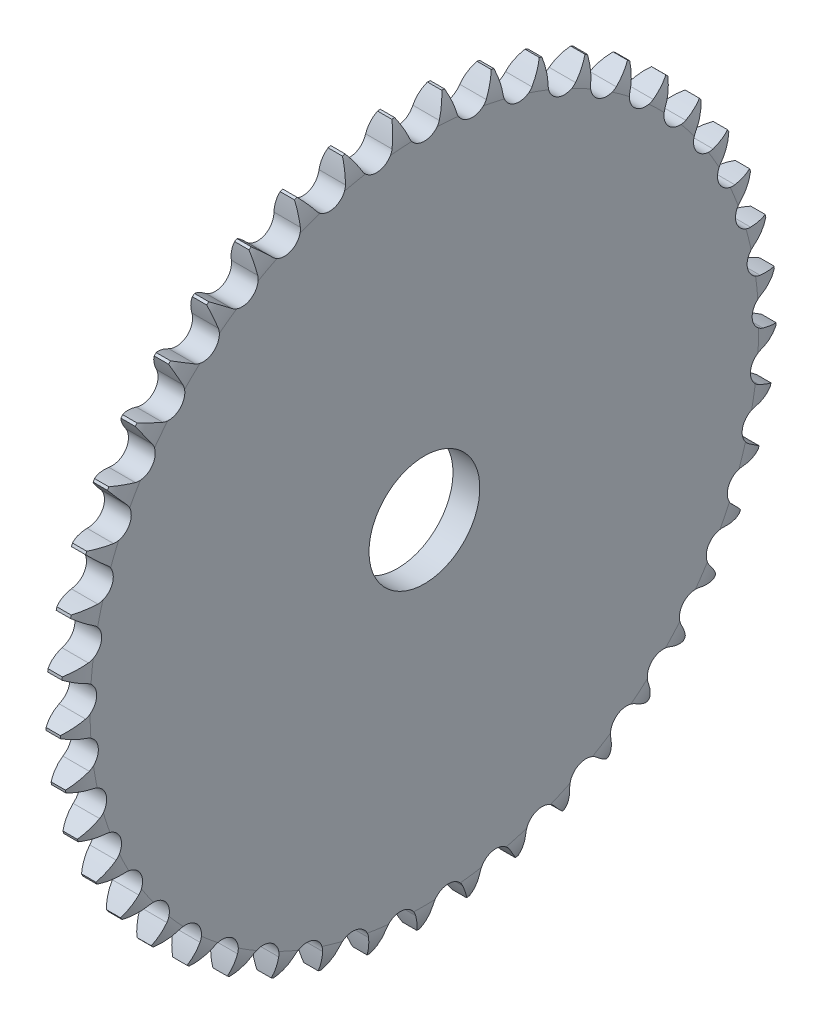
SolidWorks part; units mm, degrees
ref_plane "Plane1" through (0, 0, 0) normal (0, 0, 1) x (1, 0, 0)
ref_plane "Plane2" through (0, 0, 0) normal (0, 1, 0) x (1, 0, 0)
ref_plane "Plane3" through (0, 0, 0) normal (1, 0, 0) x (0, 0, -1)
sketch "Clipboard" plane through (0, 0, 0) normal (0, 1, 0) x (1, 0, 0)
  line L0 (0, 0) -> (6.7352, -6.7352)
  line L1 (-15, 0) -> (100, 0) construction
  line L2 (0, 0) -> (-0.8203, 0.9272)
  line L3 (0, 0) -> (-8.8973, 3.4006)
  line L4 (0, 0) -> (2.192, 2.192)
  line L5 (0, 0) -> (-46.8476, -17.4728)
  line L6 (0, 0) -> (-4.4098, -2.9753)
  line L7 (-0.8203, 0.9272) -> (33.9129, 36.8945)
  line L8 (-76.2, 38.1) -> (-72.9, 38.1)
  line L9 (-73.3242, 40.7328) -> (-72.926, 40.7699)
  line L10 (-73.4529, 9.1872) -> (-63.2129, 9.1872)
  circle A0 centre (0, 0) radius 3.175
  circle A1 centre (0, 0) radius 37.5
  circle A2 centre (0, 0) radius 37.5
  dimension "Dr" = 6.35
  dimension "MHD" = 75
  dimension "Hub_dia" = 75
  dimension "Num_teeth" = 45
  dimension "Pitch" = 9.525
  dimension "Width" = 3.1
  dimension "Side_relief" = 1.238
  dimension "Side_radius" = 9.525
  dimension "Overall_len" = 50
  dimension "Show_teeth" = 45
  dimension "Thickness" = 5.3196
  dimension "OAL" = 50.0005
  dimension "T_dim" = 3.3
  dimension "Fillet_rad" = 0.4
  dimension "Face_width" = 5.32
  dimension "Num_strands" = 1
  dimension "Transv_pitch" = 10.24
  dimension "Plate_wid" = 8.26
sketch "BasProSke" plane through (0, 0, 0) normal (0, 1, 0) x (1, 0, 0)
  line L0 (-10, 0) -> (60, 0) construction
  line L1 (0, 0) -> (0, 66.3555)
  line L2 (0, 0) -> (5.3196, 0)
  line L3 (5.3196, 0) -> (5.3196, 66.3555)
  line L4 (4.0816, 71.0514) -> (1.238, 71.0514)
  arc A0 (0, 66.3555) -> (1.238, 71.0514) centre (9.525, 66.3555) cw
  arc A1 (5.3196, 66.3555) -> (4.0816, 71.0514) centre (-4.2054, 66.3555) ccw
  dimension "Thickness" = 5.3196
  dimension "D1" = 9.525
  dimension "G1" = 1.238
  dimension "G2" = 1.238
  dimension "Diameter" = 142.1027
revolve "Base-Revolve" add sketch "BasProSke" angle 360 about L0
sketch "TooCutSke" plane through (0, 0, 0) normal (1, 0, 0) x (0, 0, -1)
  line L0 (0, 68.305) -> (2.9938, 67.1558) construction
  line L1 (0, 0) -> (0, 107) construction
  line L2 (0, 68.305) -> (-10, 68.305) construction
  line L3 (0, 68.305) -> (-2.9938, 67.1558) construction
  arc A0 (2.9938, 67.1558) -> (4.9391, 71.3807) centre (36.429, 54.3212) cw
  arc A1 (2.9938, 67.1558) -> (-2.9938, 67.1558) centre (0, 68.305) cw
  arc A2 (-2.9938, 67.1558) -> (-4.9391, 71.3807) centre (-36.429, 54.3212) ccw
  arc A3 (4.9391, 71.3807) -> (-4.9391, 71.3807) centre (0, 0) ccw
  dimension "R1" = 3.2067
  dimension "R2" = 35.814
  dimension "Overcut" = 71.5514
  dimension "Seat_radius" = 68.305
  dimension "X" = 138
extrude "ToothCut" cut sketch "TooCutSke" along normal through all
pattern_circular "TeethCuts" count 45 every 8 about axis through (-10, 0, 0) along (1, 0, 0) of "ToothCut"
sketch "HubNeaOneSke" plane through (0, 0, 0) normal (-1, 0, 0) x (0, 0, 1)
  circle A0 centre (0, 0) radius 37.5
  dimension "Diameter" = 75
extrude "HubNearOne" [suppressed] add sketch "HubNeaOneSke" along normal blind 44.6809
fillet "HubNearOneFillet" [suppressed] radius 0.4
sketch "HubNeaBotSke" plane through (0, 0, 0) normal (-1, 0, 0) x (0, 0, 1)
  circle A0 centre (0, 0) radius 37.5
  dimension "Diameter" = 75
extrude "HubNearBoth" [suppressed] add sketch "HubNeaBotSke" along normal blind 22.3405
fillet "HubNearBothFillet" [suppressed] radius 0.4
ref_plane "FarPln" through (5.3196, 0, 0) normal (1, 0, 0) x (0, 0, -1)
sketch "HubFarSke" plane through (5.3196, 0, 0) normal (1, 0, 0) x (0, 0, -1)
  circle A0 centre (0, 0) radius 37.5
  dimension "Diameter" = 75
extrude "HubFar" [suppressed] add sketch "HubFarSke" along normal blind 22.3405
fillet "HubFarFillet" [suppressed] radius 0.4
sketch "BorSke" plane through (0, 0, 0) normal (1, 0, 0) x (0, 0, -1)
  circle A0 centre (0, 0) radius 11
  dimension "Diameter" = 22
extrude "Bore" cut sketch "BorSke" along normal mid plane 100.001
sketch "KeySke" plane through (0, 0, 0) normal (1, 0, 0) x (0, 0, -1)
  line L0 (-3, 0) -> (-3, 14.3)
  line L1 (-3, 14.3) -> (3, 14.3)
  line L2 (3, 14.3) -> (3, 0)
  line L3 (0, 0) -> (0, 34) construction
  line L4 (-3, 0) -> (3, 0)
  dimension "Offset" = 14.3
  dimension "Width" = 6
extrude "Keyway" [suppressed] cut sketch "KeySke" along normal mid plane 100.001
pattern_circular "Keyway2" [suppressed] count 2 every 90 about axis through (-10, 0, 0) along (1, 0, 0)
equation "' \"Pitch@Clipboard\" = 12.7"
equation "' \"Num_strands@Clipboard\" = 1"
equation "' \"Num_teeth@Clipboard\" = 9"
equation "' \"Hub_dia@Clipboard\" = 50"
equation "' \"Overall_len@Clipboard\" = 3"
equation "' \"Diameter@BorSke\" = 12"
equation "' \"T_dim@Clipboard\" = 1"
equation "' \"Width@KeySke\" = 2"
equation "' \"Dr@Clipboard\" = 8.51"
equation "' \"Face_width@Clipboard\" = 7.2"
equation "' \"Side_radius@Clipboard\" = 12.7"
equation "' \"Side_relief@Clipboard\" = 1.27"
equation "' \"Transv_pitch@Clipboard\" = 13.92"
equation "' \"Show_teeth@Clipboard\" = 9"
equation "' \"Fillet_rad@Clipboard\" = 0.6"
equation "' \"Plate_wid@Clipboard\" = 11.8"
equation "\"Num_teeth@Clipboard\" = int( \"Num_teeth@Clipboard\" )"
equation "\"Num_teeth@Clipboard\" = ((sgn( \"Num_teeth@Clipboard\" - 5.0)+1)*( \"Num_teeth@Clipboard\" - 5.0))/2 +5.0"
equation "\"Num_teeth@Clipboard\" = ((sgn( \"Num_teeth@Clipboard\" - 200.0)-1)*( \"Num_teeth@Clipboard\" - 200.0))/-2 +200.0"
equation "\"MHD@Clipboard\" = \"Pitch@Clipboard\" * (1.0 / tan(3.14159265 / \"Num_teeth@Clipboard\" )) - 1.04 * \"Plate_wid@Clipboard\" - 0.76"
equation "\"Thickness@Clipboard\"  = \"Face_width@Clipboard\" + (\"Num_strands@Clipboard\" - 1) * \"Transv_pitch@Clipboard\""
equation "\"OAL@Clipboard\" = \"Thickness@Clipboard\" + 2 * \"Fillet_rad@Clipboard\" + 1"
equation "\"MHD@Clipboard\" = ((sgn( \"MHD@Clipboard\" - \"Hub_dia@Clipboard\" )-1)*( \"MHD@Clipboard\" - \"Hub_dia@Clipboard\" ))/-2+ \"Hub_dia@Clipboard\""
equation "\"OAL@Clipboard\" = ((sgn( \"OAL@Clipboard\" - \"Overall_len@Clipboard\" )+1)*( \"OAL@Clipboard\" - \"Overall_len@Clipboard\" ))/2 + \"Overall_len@Clipboard\" + 0.0005"
equation "\"Num_teeth@TeethCuts\" = int( \"Show_teeth@Clipboard\" ) + 1"
equation "\"Num_teeth@TeethCuts\" = ((sgn( \"Num_teeth@TeethCuts\" - \"Num_teeth@Clipboard\" )-1)*( \"Num_teeth@TeethCuts\" - \"Num_teeth@Clipboard\" ))/-2+ \"Num_teeth@Clipboard\""
equation "\"Num_teeth@TeethCuts\" = ((sgn( \"Num_teeth@TeethCuts\" - 2.0)+1)*( \"Num_teeth@TeethCuts\" - 2.0))/2 +2.0"
equation "\"Angle@TeethCuts\" = 360.0 / \"Num_teeth@Clipboard\""
equation "\"Seat_radius@TooCutSke\" = ( \"Pitch@Clipboard\" / 2.0) / sin(3.14159265 / \"Num_teeth@Clipboard\" ) - \"Dr@Clipboard\" / 2.0 + \"Dr@Clipboard\" * 0.505"
equation "\"R1@TooCutSke\"  = \"Dr@Clipboard\" * 0.505"
equation "\"X@TooCutSke\" = 140.0 - (90.0 / \"Num_teeth@Clipboard\")"
equation "\"R2@TooCutSke\" = 0.12 * \"Dr@Clipboard\" * ( \"Num_teeth@Clipboard\" + 2.0)"
equation "\"Overcut@TooCutSke\" = 0.5 + 0.625 * \"Pitch@Clipboard\" - 0.5 * \"Dr@Clipboard\"  +  \"Pitch@Clipboard\" / 2.0 / sin(3.14159265 / \"Num_teeth@Clipboard\" )"
equation "\"Diameter@BasProSke\" = 2.0 * ( 0.625 * \"Pitch@Clipboard\" - 0.5 * \"Dr@Clipboard\"  +  \"Pitch@Clipboard\" / 2.0 / sin(3.14159265 / \"Num_teeth@Clipboard\" ))"
equation "\"Thickness@BasProSke\"  = \"Thickness@Clipboard\""
equation "\"G1@BasProSke\" =  \"Side_relief@Clipboard\""
equation "\"G2@BasProSke\" =  \"Side_relief@Clipboard\""
equation "\"D1@BasProSke\" =  \"Side_radius@Clipboard\""
equation "\"Diameter@HubNeaOneSke\" = \"MHD@Clipboard\""
equation "\"Length@HubNearOne\" = \"OAL@Clipboard\" - \"Thickness@BasProSke\""
equation "\"Diameter@HubNeaBotSke\" = \"MHD@Clipboard\""
equation "\"Length@HubNearBoth\" = ( \"OAL@Clipboard\" - \"Thickness@BasProSke\" ) / 2.0"
equation "\"D1@HubNearOneFillet\" = \"Fillet_rad@Clipboard\""
equation "\"D1@HubNearBothFillet\" = \"Fillet_rad@Clipboard\""
equation "\"Thickness@FarPln\" = \"Thickness@BasProSke\""
equation "\"Diameter@HubFarSke\" = \"MHD@Clipboard\""
equation "\"Length@HubFar\" = ( \"OAL@Clipboard\" - \"Thickness@BasProSke\" ) / 2.0"
equation "\"D1@HubFarFillet\" = \"Fillet_rad@Clipboard\""
equation "\"D1@Bore\" = \"OAL@Clipboard\" * 2.0"
equation "\"D1@Keyway\" = \"OAL@Clipboard\" * 2.0"
equation "\"Offset@KeySke\" = \"T_dim@Clipboard\" + \"Diameter@BorSke\" / 2.0"
